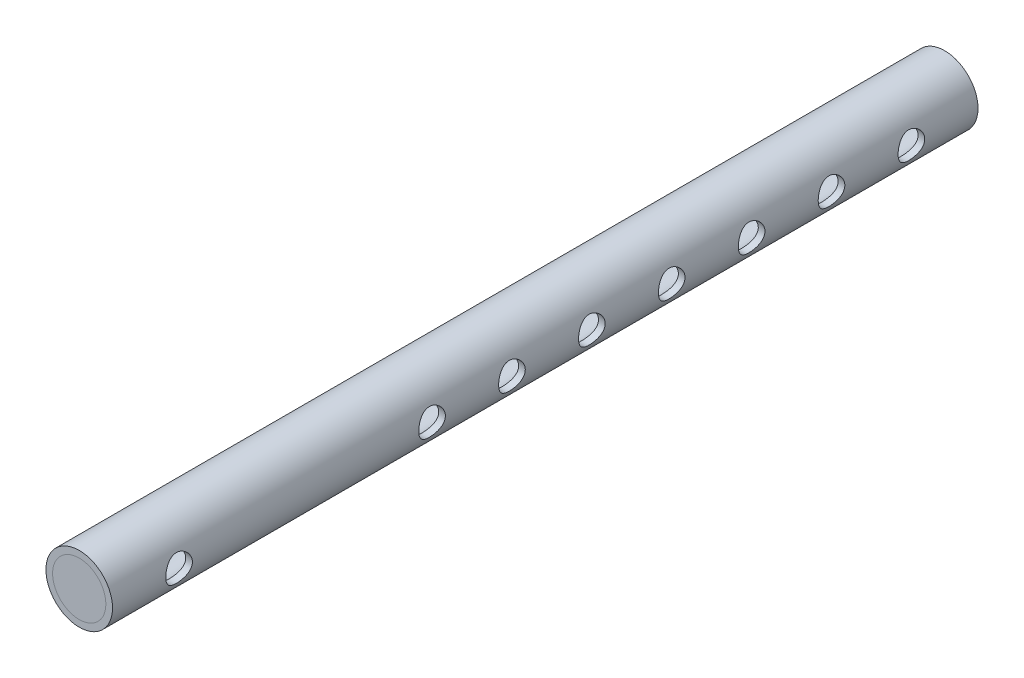
SolidWorks part; units mm, degrees
material "Cedar"
ref_plane "Front Plane" through (0, 0, 0) normal (0, 0, 1) x (1, 0, 0)
ref_plane "Top Plane" through (0, 0, 0) normal (0, 1, 0) x (1, 0, 0)
ref_plane "Right Plane" through (0, 0, 0) normal (1, 0, 0) x (0, 0, -1)
sketch "Sketch1" plane through (0, 0, 0) normal (0, 0, 1) x (1, 0, 0)
  circle A0 centre (0, 0) radius 12.5
  circle A1 centre (0, 0) radius 10
  dimension "D1" = 25
  dimension "D2" = 20
extrude "Boss-Extrude1" add sketch "Sketch1" along normal blind 325
sketch "Sketch2" plane through (0, 0, 325) normal (0, 0, 1) x (1, 0, 0)
  circle A0 centre (0, 0) radius 10 construction
  circle A1 centre (0, 0) radius 10
extrude "Boss-Extrude2" add sketch "Sketch2" against normal blind 5 separate body
sketch "Sketch3" plane through (0, 0, 0) normal (1, 0, 0) x (0, 0, -1)
  line L0 (-325, 12.5) -> (-325, -12.5) construction
  line L1 (-325, -12.5) -> (0, -12.5) construction
  circle A0 centre (-300, 0) radius 5
  dimension "D3" = 10
  dimension "D1" = 25
  dimension "D2" = 12.5
extrude "Cut-Extrude1" cut sketch "Sketch3" along normal through all
sketch "Sketch4" plane through (0, 0, 0) normal (1, 0, 0) x (0, 0, -1)
  line L0 (-325, 0) -> (-215.7405, 0) construction
  line L1 (-325, 12.5) -> (-325, -12.5) construction
  circle A0 centre (-205, 0) radius 5
  circle A1 centre (-300, 0) radius 5 construction
  point P9 (0, 0)
  dimension "D2" = 10
  dimension "D1" = 95
extrude "Cut-Extrude2" cut sketch "Sketch4" along normal through all
pattern_linear "LPattern1" count 7 spacing 30 along (0, 0, -1) of "Cut-Extrude2"
